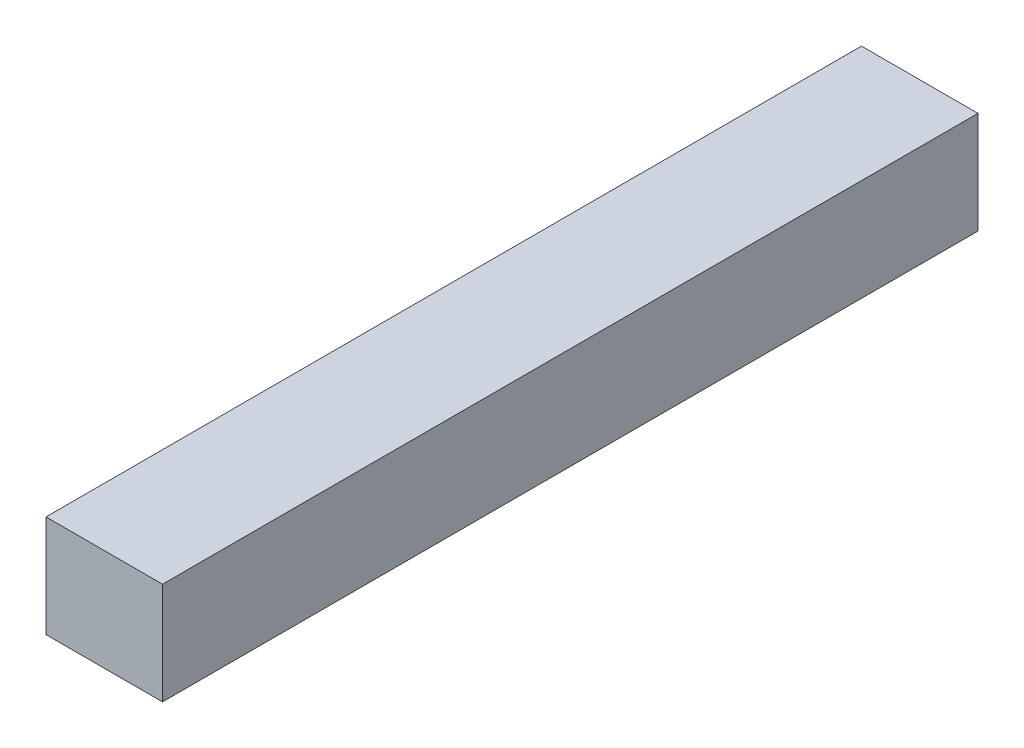
SolidWorks part; units mm, degrees
ref_plane "Front Plane" through (0, 0, 0) normal (0, 0, 1) x (1, 0, 0)
ref_plane "Top Plane" through (0, 0, 0) normal (0, 1, 0) x (1, 0, 0)
ref_plane "Right Plane" through (0, 0, 0) normal (1, 0, 0) x (0, 0, -1)
sketch "Sketch1" plane through (0, 0, 0) normal (0, 0, 1) x (1, 0, 0)
  line L1 (-4, -3.5) -> (4, -3.5)
  line L2 (-4, -3.5) -> (-4, 3.5)
  line L3 (-4, 3.5) -> (4, 3.5)
  line L4 (4, -3.5) -> (4, 3.5)
  line L5 (-4, -3.5) -> (4, 3.5) construction
  line L6 (-4, 3.5) -> (4, -3.5) construction
  point P0 (0, 0)
  dimension "D1" = 8
  dimension "D2" = 7
extrude "Boss-Extrude1" add sketch "Sketch1" along normal mid plane 56
